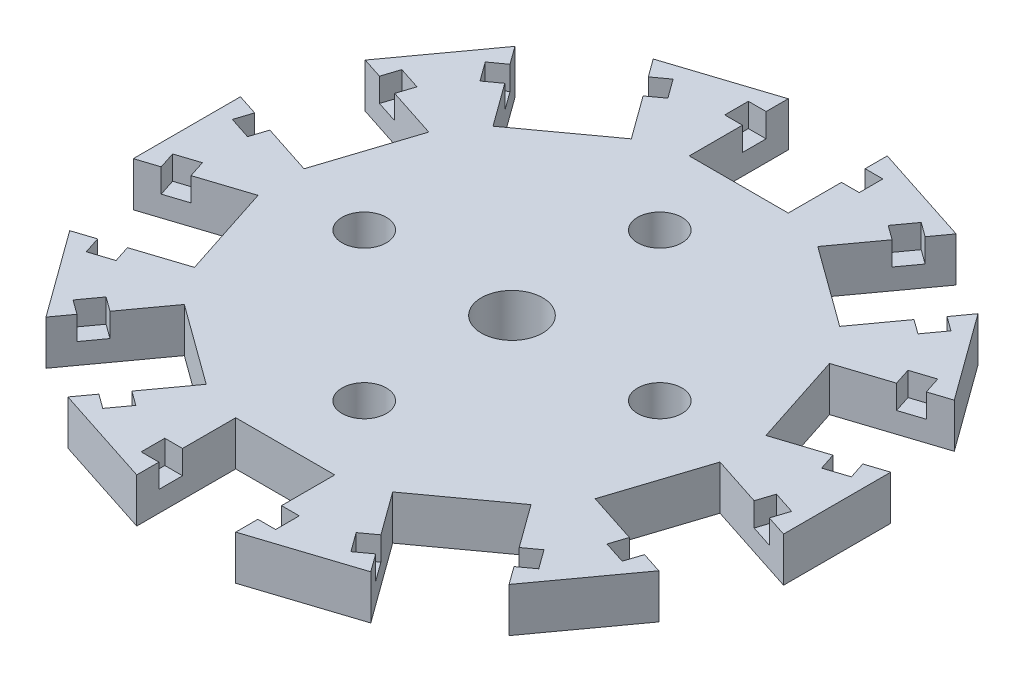
SolidWorks part; units mm, degrees
ref_plane "Front Plane" through (0, 0, 0) normal (0, 0, 1) x (1, 0, 0)
ref_plane "Top Plane" through (0, 0, 0) normal (0, 1, 0) x (1, 0, 0)
ref_plane "Right Plane" through (0, 0, 0) normal (1, 0, 0) x (0, 0, -1)
sketch "Sketch1" plane through (0, 0, 0) normal (0, 1, 0) x (1, 0, 0)
  line L1 (0, 23.1322) -> (-13.5967, 18.7143)
  line L2 (-13.5967, 18.7143) -> (-22, 7.1482)
  line L3 (-22, 7.1482) -> (-22, -7.1482)
  line L4 (-22, -7.1482) -> (-13.5967, -18.7143)
  line L5 (-13.5967, -18.7143) -> (0, -23.1322)
  line L6 (0, -23.1322) -> (13.5967, -18.7143)
  line L7 (13.5967, -18.7143) -> (22, -7.1482)
  line L8 (22, -7.1482) -> (22, 7.1482)
  line L9 (22, 7.1482) -> (13.5967, 18.7143)
  line L10 (13.5967, 18.7143) -> (0, 23.1322)
  circle A0 centre (0, 0) radius 22 construction
  dimension "D1" = 44
extrude "Boss-Extrude1" add sketch "Sketch1" along normal blind 3
sketch "Sketch2" plane through (0, 3, 0) normal (0, 1, 0) x (1, 0, 0)
  line L0 (0, 23.1322) -> (-3.35, 22.0437)
  line L1 (0, 23.1322) -> (-13.5967, 18.7143) construction
  line L2 (-3.35, 22.0437) -> (-3.35, 15.3437)
  line L3 (-3.35, 15.3437) -> (3.35, 15.3437)
  line L4 (3.35, 15.3437) -> (3.35, 22.0437)
  line L5 (13.5967, 18.7143) -> (0, 23.1322) construction
  line L6 (3.35, 22.0437) -> (0, 23.1322)
  line L7 (11.729, 10.4442) -> (15.6672, 15.8646)
  line L8 (15.6672, 15.8646) -> (13.5967, 18.7143)
  line L9 (13.5967, 18.7143) -> (10.2467, 19.8028)
  line L10 (10.2467, 19.8028) -> (6.3086, 14.3824)
  line L11 (6.3086, 14.3824) -> (11.729, 10.4442)
  line L12 (15.6279, 1.5554) -> (22, 3.6258)
  line L13 (22, 3.6258) -> (22, 7.1482)
  line L14 (22, 7.1482) -> (19.9296, 9.9979)
  line L15 (19.9296, 9.9979) -> (13.5575, 7.9275)
  line L16 (13.5575, 7.9275) -> (15.6279, 1.5554)
  line L17 (13.5575, -7.9275) -> (19.9296, -9.9979)
  line L18 (19.9296, -9.9979) -> (22, -7.1482)
  line L19 (22, -7.1482) -> (22, -3.6258)
  line L20 (22, -3.6258) -> (15.6279, -1.5554)
  line L21 (15.6279, -1.5554) -> (13.5575, -7.9275)
  line L22 (6.3086, -14.3824) -> (10.2467, -19.8028)
  line L23 (10.2467, -19.8028) -> (13.5967, -18.7143)
  line L24 (13.5967, -18.7143) -> (15.6672, -15.8646)
  line L25 (15.6672, -15.8646) -> (11.729, -10.4442)
  line L26 (11.729, -10.4442) -> (6.3086, -14.3824)
  line L27 (-3.35, -15.3437) -> (-3.35, -22.0437)
  line L28 (-3.35, -22.0437) -> (0, -23.1322)
  line L29 (0, -23.1322) -> (3.35, -22.0437)
  line L30 (3.35, -22.0437) -> (3.35, -15.3437)
  line L31 (3.35, -15.3437) -> (-3.35, -15.3437)
  line L32 (-11.729, -10.4442) -> (-15.6672, -15.8646)
  line L33 (-15.6672, -15.8646) -> (-13.5967, -18.7143)
  line L34 (-13.5967, -18.7143) -> (-10.2467, -19.8028)
  line L35 (-10.2467, -19.8028) -> (-6.3086, -14.3824)
  line L36 (-6.3086, -14.3824) -> (-11.729, -10.4442)
  line L37 (-15.6279, -1.5554) -> (-22, -3.6258)
  line L38 (-22, -3.6258) -> (-22, -7.1482)
  line L39 (-22, -7.1482) -> (-19.9296, -9.9979)
  line L40 (-19.9296, -9.9979) -> (-13.5575, -7.9275)
  line L41 (-13.5575, -7.9275) -> (-15.6279, -1.5554)
  line L42 (-13.5575, 7.9275) -> (-19.9296, 9.9979)
  line L43 (-19.9296, 9.9979) -> (-22, 7.1482)
  line L44 (-22, 7.1482) -> (-22, 3.6258)
  line L45 (-22, 3.6258) -> (-15.6279, 1.5554)
  line L46 (-15.6279, 1.5554) -> (-13.5575, 7.9275)
  line L47 (-6.3086, 14.3824) -> (-10.2467, 19.8028)
  line L48 (-10.2467, 19.8028) -> (-13.5967, 18.7143)
  line L49 (-13.5967, 18.7143) -> (-15.6672, 15.8646)
  line L50 (-15.6672, 15.8646) -> (-11.729, 10.4442)
  line L51 (-11.729, 10.4442) -> (-6.3086, 14.3824)
  point P5 (0, 15.3437)
  point P59 (0, 0)
  dimension "D1" = 6.7
  dimension "D2" = 6.7
  dimension "D3" = 10
extrude "Cut-Extrude1" cut sketch "Sketch2" against normal up to surface (3 mm away) up to face at (0, 0, 0)
sketch "Sketch7" plane through (0, 3, 0) normal (0, 1, 0) x (1, 0, 0)
  circle A0 centre (0, 0) radius 10 construction
  circle A1 centre (0, 10) radius 1.5
  circle A2 centre (10, 0) radius 1.5
  circle A3 centre (0, -10) radius 1.5
  circle A4 centre (-10, 0) radius 1.5
  dimension "D1" = 20
  dimension "D2" = 3
extrude "Cut-Extrude3" cut sketch "Sketch7" against normal up to surface (3 mm away) up to face at (0, 0, 0)
sketch "Sketch10" plane through (0, 3, 0) normal (0, 1, 0) x (1, 0, 0)
  circle A0 centre (0, 0) radius 2.075
  dimension "D1" = 4.15
extrude "Cut-Extrude6" cut sketch "Sketch10" against normal up to surface (3 mm away) up to face at (0, 0, -8.5)
sketch "Sketch4" plane through (0, 3, 0) normal (0, 1, 0) x (1, 0, 0)
  line L0 (-3.35, 15.3437) -> (3.35, 15.3437) construction
  line L1 (-4.55, 18.9437) -> (4.55, 18.9437)
  line L2 (-4.55, 18.9437) -> (-4.55, 20.5437)
  line L3 (-4.55, 20.5437) -> (4.55, 20.5437)
  line L4 (4.55, 18.9437) -> (4.55, 20.5437)
  line L5 (-4.55, 18.9437) -> (4.55, 20.5437) construction
  line L6 (-4.55, 20.5437) -> (4.55, 18.9437) construction
  line L7 (7.4538, 18.0002) -> (8.3942, 19.2946)
  line L8 (7.4538, 18.0002) -> (14.8158, 12.6513)
  line L9 (14.8158, 12.6513) -> (15.7563, 13.9458)
  line L10 (8.3942, 19.2946) -> (15.7563, 13.9458)
  line L11 (16.6105, 10.1812) -> (18.1322, 10.6757)
  line L12 (16.6105, 10.1812) -> (19.4225, 1.5266)
  line L13 (19.4225, 1.5266) -> (20.9442, 2.021)
  line L14 (18.1322, 10.6757) -> (20.9442, 2.021)
  line L15 (19.4225, -1.5266) -> (20.9442, -2.021)
  line L16 (19.4225, -1.5266) -> (16.6105, -10.1812)
  line L17 (16.6105, -10.1812) -> (18.1322, -10.6757)
  line L18 (20.9442, -2.021) -> (18.1322, -10.6757)
  line L19 (14.8158, -12.6513) -> (15.7563, -13.9458)
  line L20 (14.8158, -12.6513) -> (7.4538, -18.0002)
  line L21 (7.4538, -18.0002) -> (8.3942, -19.2946)
  line L22 (15.7563, -13.9458) -> (8.3942, -19.2946)
  line L23 (4.55, -18.9437) -> (4.55, -20.5437)
  line L24 (4.55, -18.9437) -> (-4.55, -18.9437)
  line L25 (-4.55, -18.9437) -> (-4.55, -20.5437)
  line L26 (4.55, -20.5437) -> (-4.55, -20.5437)
  line L27 (-7.4538, -18.0002) -> (-8.3942, -19.2946)
  line L28 (-7.4538, -18.0002) -> (-14.8158, -12.6513)
  line L29 (-14.8158, -12.6513) -> (-15.7563, -13.9458)
  line L30 (-8.3942, -19.2946) -> (-15.7563, -13.9458)
  line L31 (-16.6105, -10.1812) -> (-18.1322, -10.6757)
  line L32 (-16.6105, -10.1812) -> (-19.4225, -1.5266)
  line L33 (-19.4225, -1.5266) -> (-20.9442, -2.021)
  line L34 (-18.1322, -10.6757) -> (-20.9442, -2.021)
  line L35 (-19.4225, 1.5266) -> (-20.9442, 2.021)
  line L36 (-19.4225, 1.5266) -> (-16.6105, 10.1812)
  line L37 (-16.6105, 10.1812) -> (-18.1322, 10.6757)
  line L38 (-20.9442, 2.021) -> (-18.1322, 10.6757)
  line L39 (-14.8158, 12.6513) -> (-15.7563, 13.9458)
  line L40 (-14.8158, 12.6513) -> (-7.4538, 18.0002)
  line L41 (-7.4538, 18.0002) -> (-8.3942, 19.2946)
  line L42 (-15.7563, 13.9458) -> (-8.3942, 19.2946)
  point P0 (0, 19.7437)
  point P46 (0, 0)
  dimension "D1" = 9.1
  dimension "D2" = 1.6
  dimension "D3" = 4.4
  dimension "D4" = 10
extrude "Cut-Extrude2" cut sketch "Sketch4" against normal blind 1.6
sketch "Sketch8" plane through (0, 0, 0) normal (0, -1, 0) x (1, 0, 0)
  circle A0 centre (0, 0) radius 13
  dimension "D1" = 26
extrude "Cut-Extrude4" [suppressed] cut sketch "Sketch8" against normal blind 1
sketch "Sketch9" plane through (0, 3, 0) normal (0, 1, 0) x (1, 0, 0)
  circle A0 centre (0, 10) radius 3.05
  circle A1 centre (10, 0) radius 3.05
  circle A2 centre (0, -10) radius 3.05
  circle A3 centre (-10, 0) radius 3.05
  dimension "D1" = 6.1
extrude "Cut-Extrude5" [suppressed] cut sketch "Sketch9" against normal blind 1
equation "\"E\"=10"
